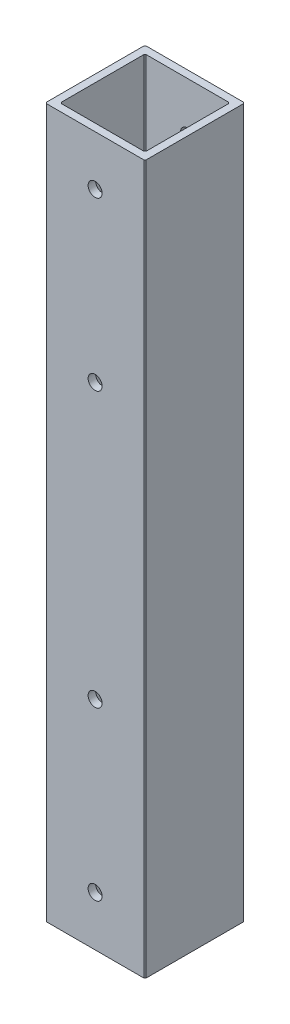
SolidWorks part; units mm, degrees
ref_plane "Front Plane" through (0, 0, 0) normal (0, 0, 1) x (1, 0, 0)
ref_plane "Top Plane" through (0, 0, 0) normal (0, 1, 0) x (1, 0, 0)
ref_plane "Right Plane" through (0, 0, 0) normal (1, 0, 0) x (0, 0, -1)
ref_plane "Plane1" through (0, 0, 180) normal (0, 0, 1) x (1, 0, 0)
sketch "Sketch1" plane through (0, 0, 180) normal (0, 0, 1) x (1, 0, 0)
  line L0 (80, -142) -> (120, -142)
  line L1 (120, -142) -> (120, 142)
  line L2 (120, 142) -> (80, 142)
  line L3 (80, 142) -> (80, -142)
extrude "Boss-Extrude1" add sketch "Sketch1" against normal blind 40
sketch "Sketch2" plane through (0, -142, 0) normal (0, -1, 0) x (1, 0, 0)
  line L0 (117, 143) -> (117, 177)
  line L1 (117, 177) -> (83, 177)
  line L2 (83, 177) -> (83, 143)
  line L3 (83, 143) -> (117, 143)
extrude "Cut-Extrude1" cut sketch "Sketch2" against normal through all
hole_wizard "Ø5.6 (5.6) Diameter Hole1" positions "Sketch4" profile "Sketch3" hole size "Ø5.6" standard "ANSI Metric"
sketch "Sketch4" plane through (0, 0, 140) normal (0, 0, -1) x (-1, 0, 0)
  point P0 (-100, 122)
  point P1 (-100, 55)
  point P2 (-100, -55)
  point P3 (-100, -122)
sketch "Sketch3" plane through (100, 122, 140) normal (1, 0, 0) x (0, 1, 0)
  line L0 (0, 0) -> (0, 3)
  line L1 (0, 3) -> (2.8, 3)
  line L2 (2.8, 3) -> (2.8, 0)
  line L5 (2.8, 0) -> (0, 0)
  line L11 (0, -6.35) -> (0, 107.95) construction
  dimension "Thru Hole Dia." = 5.6
  dimension "Thru Hole Depth" = 3
hole_wizard "Ø5.6 (5.6) Diameter Hole2" positions "Sketch6" profile "Sketch5" hole size "Ø5.6" standard "ANSI Metric"
sketch "Sketch6" plane through (0, 0, 177) normal (0, 0, -1) x (-1, 0, 0)
  point P0 (-100, 122)
  point P1 (-100, 55)
  point P2 (-100, -55)
  point P3 (-100, -122)
sketch "Sketch5" plane through (100, 122, 177) normal (1, 0, 0) x (0, 1, 0)
  line L0 (0, 0) -> (0, 3)
  line L1 (0, 3) -> (2.8, 3)
  line L2 (2.8, 3) -> (2.8, 0)
  line L5 (2.8, 0) -> (0, 0)
  line L11 (0, -6.35) -> (0, 107.95) construction
  dimension "Thru Hole Dia." = 5.6
  dimension "Thru Hole Depth" = 3
chamfer "Chamfer1" distance 0.5 angle 45 8 edges at (120, 0, 140) (80, 0, 140) (80, 0, 180) (83, 0, 177) (120, 0, 180) (117, 0, 143) (117, 0, 177) (83, 0, 143)
